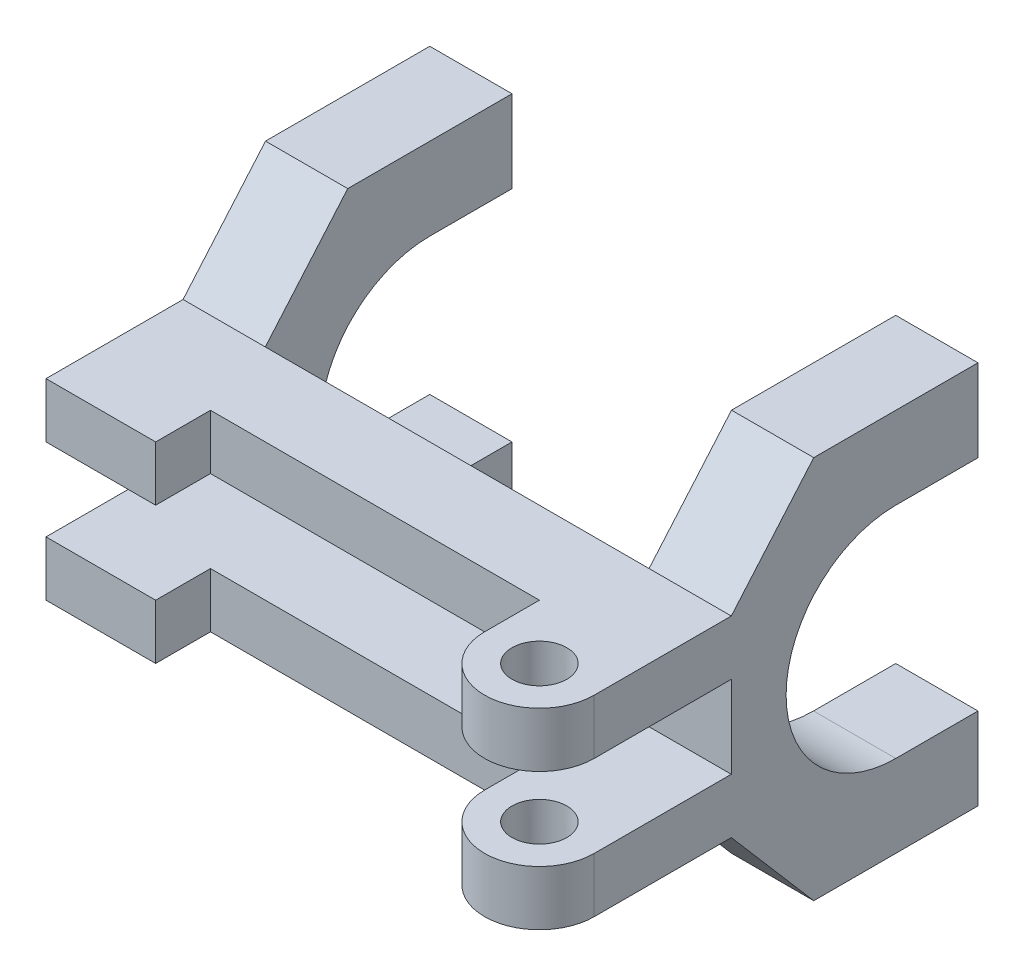
SolidWorks part; units mm, degrees
ref_plane "Front Plane" through (0, 0, 0) normal (1, 0, 0) x (0, 1, 0)
ref_plane "Top Plane" through (0, 0, 0) normal (0, 0, 1) x (0, 1, 0)
ref_plane "Right Plane" through (0, 0, 0) normal (0, 1, 0) x (-1, 0, 0)
sketch "Sketch1" plane through (0, 0, 0) normal (1, 0, 0) x (0, 1, 0)
  line L3 (0, 44.45) -> (12.7, 44.45)
  line L4 (12.7, 44.45) -> (12.7, 0)
  line L5 (12.7, 0) -> (34.925, -19.0988)
  line L6 (34.925, -19.0988) -> (34.925, -57.15)
  line L8 (0, 0) -> (-9.525, 0)
  line L9 (-9.525, 0) -> (-9.525, -12.7)
  line L10 (15.875, -38.1) -> (15.875, -57.15)
  line L11 (15.875, -57.15) -> (34.925, -57.15)
  line L12 (-9.525, -38.1) -> (-9.525, -12.7)
  line L13 (-9.525, -38.1) -> (15.875, -38.1)
  line L14 (0, 44.45) -> (0, 0)
  line L15 (12.7, 0) -> (0, 0) construction
  arc A0 (15.875, -38.1) -> (-9.525, -12.7) centre (-9.525, -38.1) ccw
  dimension "D3" = 25.4
  dimension "D1" = 44.45
  dimension "D2" = 38.0512
  dimension "D4" = 101.6
  dimension "D5" = 19.05
  dimension "D6" = 44.45
  dimension "D7" = 22.225
  dimension "D8" = 9.525
extrude "Boss-Extrude1" add sketch "Sketch1" against normal blind 127 contours A0 L10 L11 L6 L5 L4 L3 L14 L8 L9 | L15 L4 L3 L14
sketch "Sketch2" plane through (0, 12.7, 0) normal (0, 1, 0) x (-1, 0, 0)
  line L0 (127, 31.75) -> (101.6, 31.75)
  line L1 (127, 44.45) -> (127, 0) construction
  line L2 (101.6, 31.75) -> (101.6, 19.05)
  line L3 (101.6, 19.05) -> (25.4, 19.05)
  line L4 (25.4, 19.05) -> (25.4, 31.75)
  line L5 (0, 44.45) -> (0, 0) construction
  line L6 (127, 44.45) -> (0, 44.45) construction
  arc A0 (25.4, 31.75) -> (0, 31.75) centre (12.7, 31.75) ccw
  circle A1 centre (12.7, 31.75) radius 6.35
  line M4 (0, 44.45) -> (0, 0)
  line M6 (127, 0) -> (127, 44.45)
  line M7 (127, 44.45) -> (0, 44.45)
  dimension "D5" = 12.7
  dimension "D7" = 12.7
  dimension "D1" = 25.4
  dimension "D2" = 25.4
  dimension "D3" = 12.7
  dimension "D4" = 12.7
  dimension "D6" = 12.7
extrude "Cut-Extrude1" cut sketch "Sketch2" against normal through all contours A0 L4 L3 L2 L0 M6 M7 | A0 M7 M4 | A1
sketch "Sketch4" plane through (0, 34.925, 0) normal (0, 1, 0) x (-1, 0, 0)
  line L0 (19.05, -57.15) -> (19.05, 0)
  line L1 (127, -57.15) -> (0, -57.15) construction
  line L2 (19.05, 0) -> (107.95, 0)
  line L3 (107.95, 0) -> (107.95, -57.15)
  line L4 (127, 0) -> (0, 0) construction
  line L5 (0, -19.0988) -> (0, -57.15) construction
  line L6 (127, -19.0988) -> (127, -57.15) construction
  line L7 (19.05, -57.15) -> (107.95, -57.15)
  dimension "D1" = 19.05
  dimension "D2" = 19.05
extrude "Cut-Extrude2" cut sketch "Sketch4" against normal through all
mirror "Mirror1" about plane through (-127, -9.525, 0) normal (0, -1, 0) of bodies 103
